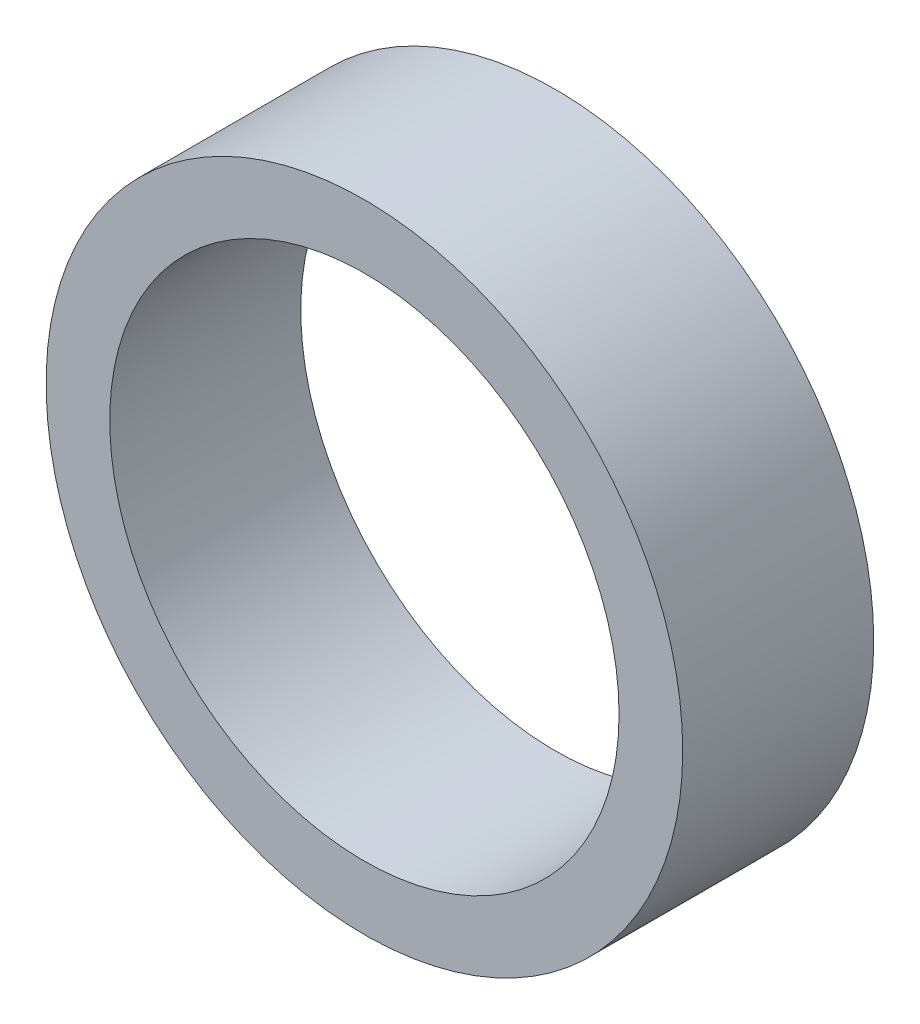
SolidWorks part; units mm, degrees
ref_plane "Front Plane" through (0, 0, 0) normal (0, 0, 1) x (1, 0, 0)
ref_plane "Top Plane" through (0, 0, 0) normal (0, 1, 0) x (1, 0, 0)
ref_plane "Right Plane" through (0, 0, 0) normal (1, 0, 0) x (0, 0, -1)
sketch "Sketch1" plane through (0, 0, 0) normal (0, 0, 1) x (1, 0, 0)
  circle A0 centre (0, 0) radius 40
  circle A1 centre (0, 0) radius 50
  point P4 (-129.6145, -36.0091)
  dimension "D1" = 80
  dimension "D2" = 100
extrude "Boss-Extrude1" add sketch "Sketch1" along normal blind 30
